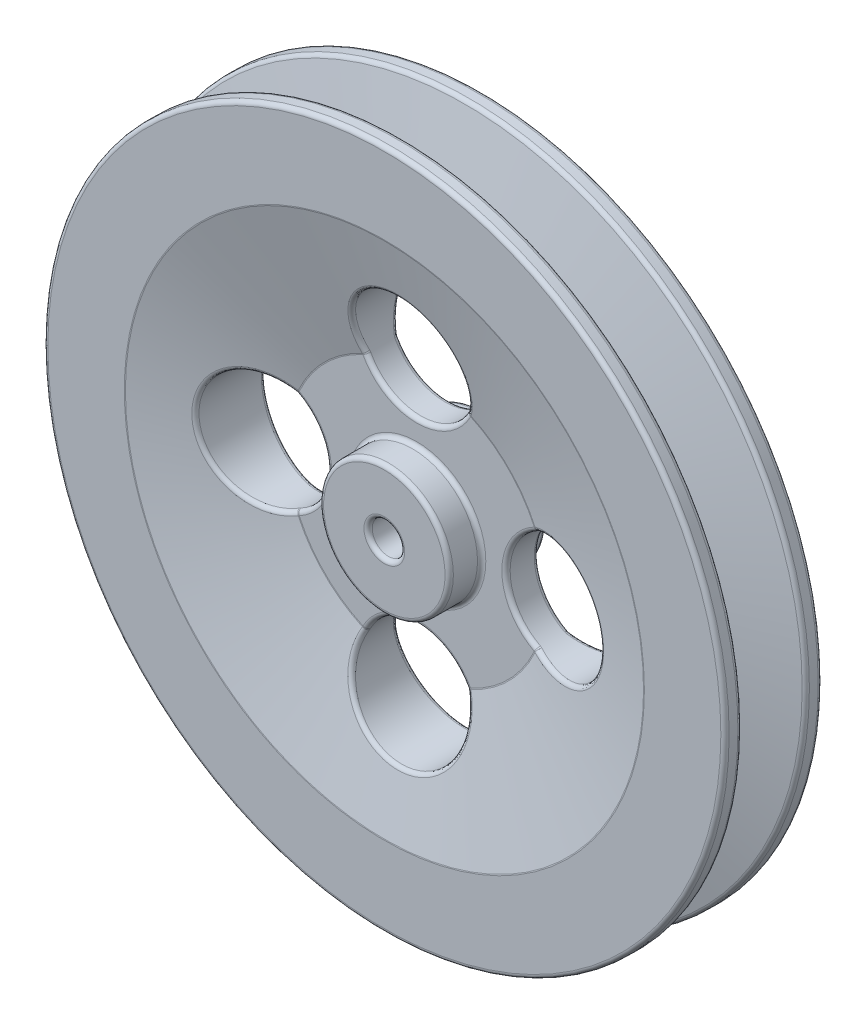
SolidWorks part; units mm, degrees
ref_plane "Front Plane" through (0, 0, 0) normal (0, 0, 1) x (1, 0, 0)
ref_plane "Top Plane" through (0, 0, 0) normal (0, 1, 0) x (1, 0, 0)
ref_plane "Right Plane" through (0, 0, 0) normal (1, 0, 0) x (0, 0, -1)
sketch "Sketch1" plane through (0, 0, 0) normal (0, 1, 0) x (1, 0, 0)
  line L0 (0, 0) -> (0, 19.05) construction
  line L1 (0, 0) -> (3.175, 0) construction
  line L2 (3.175, 0) -> (3.175, 19.05)
  line L3 (0, 0) -> (12.7, 0)
  line L4 (12.7, 0) -> (12.7, 6.35)
  line L5 (12.7, 6.35) -> (25.4, 6.35)
  line L6 (25.4, 6.35) -> (50.8, 0)
  line L7 (50.8, 0) -> (66.675, 0)
  line L8 (66.675, 0) -> (66.675, 3.175)
  line L9 (3.175, 9.525) -> (50.8, 9.525) construction
  line L10 (50.8, 12.1473) -> (50.8, 6.9027)
  line L11 (50.8, 6.9027) -> (66.675, 3.175)
  line L12 (0, 19.05) -> (3.175, 19.05) construction
  line L14 (12.7, 12.7) -> (25.4, 12.7)
  line L15 (12.7, 19.05) -> (12.7, 12.7)
  line L16 (0, 19.05) -> (12.7, 19.05)
  line L17 (50.8, 12.1473) -> (66.675, 15.875)
  line L18 (66.675, 19.05) -> (66.675, 15.875)
  line L19 (50.8, 19.05) -> (66.675, 19.05)
  line L20 (25.4, 12.7) -> (50.8, 19.05)
  dimension "D1" = 9.525
  dimension "D2" = 6.35
  dimension "D3" = 25.4
  dimension "D4" = 12.7
  dimension "D5" = 15.875
  dimension "D6" = 3.175
  dimension "D7" = 19.05
  dimension "D8" = 6.35
  dimension "D9" = 101.6
  dimension "D10" = 16.3068
revolve "Revolve8" add sketch "Sketch1" angle 360 about L0
fillet "Fillet3" radius 0.8128 16 edges at (25.4, 0, -12.7) (12.7, 0, -12.7) (12.7, 0, -19.05) (3.175, 0, -19.05) (3.175, 0, 0) (12.7, 0, 0) (12.7, 0, -6.35) (25.4, 0, -6.35) (50.8, 0, 0) (66.675, 0, 0) (66.675, 0, -3.175) (50.8, 0, -6.9027) (50.8, 0, -12.1473) (66.675, 0, -15.875) (66.675, 0, -19.05) (50.8, 0, -19.05)
sketch "Sketch2" plane through (0, 0, 0) normal (0, 0, 1) x (1, 0, 0)
  line L0 (0, 0) -> (-28.575, 0) construction
  circle A0 centre (-28.575, 0) radius 11.1125
  dimension "D1" = 22.225
  dimension "D2" = 28.575
extrude "Cut-Extrude1" cut sketch "Sketch2" against normal through all contours A0
fillet "Fillet4" radius 0.8128 8 edges at (-39.6861, -0.1765, -16.2716) (-39.6861, -0.1765, -2.7784) (-17.4625, 0, -12.7) (-17.4625, 0, -6.35)
pattern_circular "CirPattern1" count 4 over 360 about axis through (0, 0, 0) along (0, 0, 1) of "Fillet4", "Cut-Extrude1"
